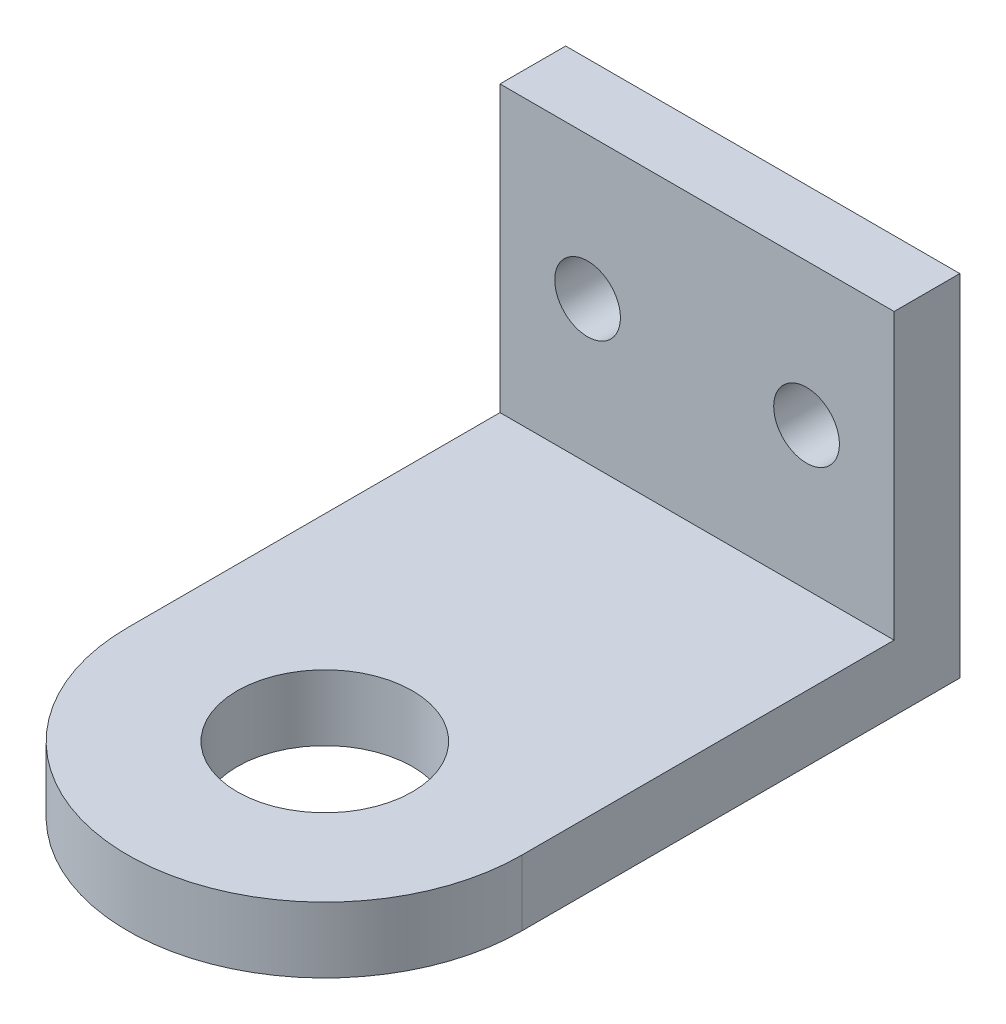
SolidWorks part; units mm, degrees
ref_plane "前视基准面" through (0, 0, 0) normal (0, 0, 1) x (1, 0, 0)
ref_plane "上视基准面" through (0, 0, 0) normal (0, 1, 0) x (1, 0, 0)
ref_plane "右视基准面" through (0, 0, 0) normal (1, 0, 0) x (0, 0, -1)
sketch "草图1" plane through (0, 0, 0) normal (0, 0, 1) x (1, 0, 0)
  line L0 (0, 8) -> (0, 0) construction
  line L1 (-9, 8) -> (9, 8)
  line L2 (-9, 8) -> (-9, -8)
  line L3 (-9, -8) -> (9, -8)
  line L4 (9, 8) -> (9, -8)
  line L5 (-9, 8) -> (9, -8) construction
  line L6 (-9, -8) -> (9, 8) construction
  line L7 (0, 0) -> (9, 0) construction
  circle A0 centre (-5, 1.5) radius 1.5
  circle A1 centre (5, 1.5) radius 1.5
  point P0 (0, 0)
  dimension "D3" = 6.5
  dimension "D4" = 4
  dimension "D5" = 3
  dimension "D1" = 16
  dimension "D2" = 18
extrude "凸台-拉伸1" add sketch "草图1" along normal blind 3
sketch "草图3" plane through (0, -8, 0) normal (0, -1, 0) x (1, 0, 0)
  line L0 (-9, 0) -> (9, 0)
  line L1 (9, 0) -> (9, 20)
  line L3 (-9, 20) -> (-9, 0)
  circle A0 centre (0, 20) radius 4
  arc A1 (9, 20) -> (-9, 20) centre (0, 20) ccw
  dimension "D2" = 8
  dimension "D3" = 9
  dimension "D1" = 20
extrude "凸台-拉伸2" add sketch "草图3" against normal blind 3
